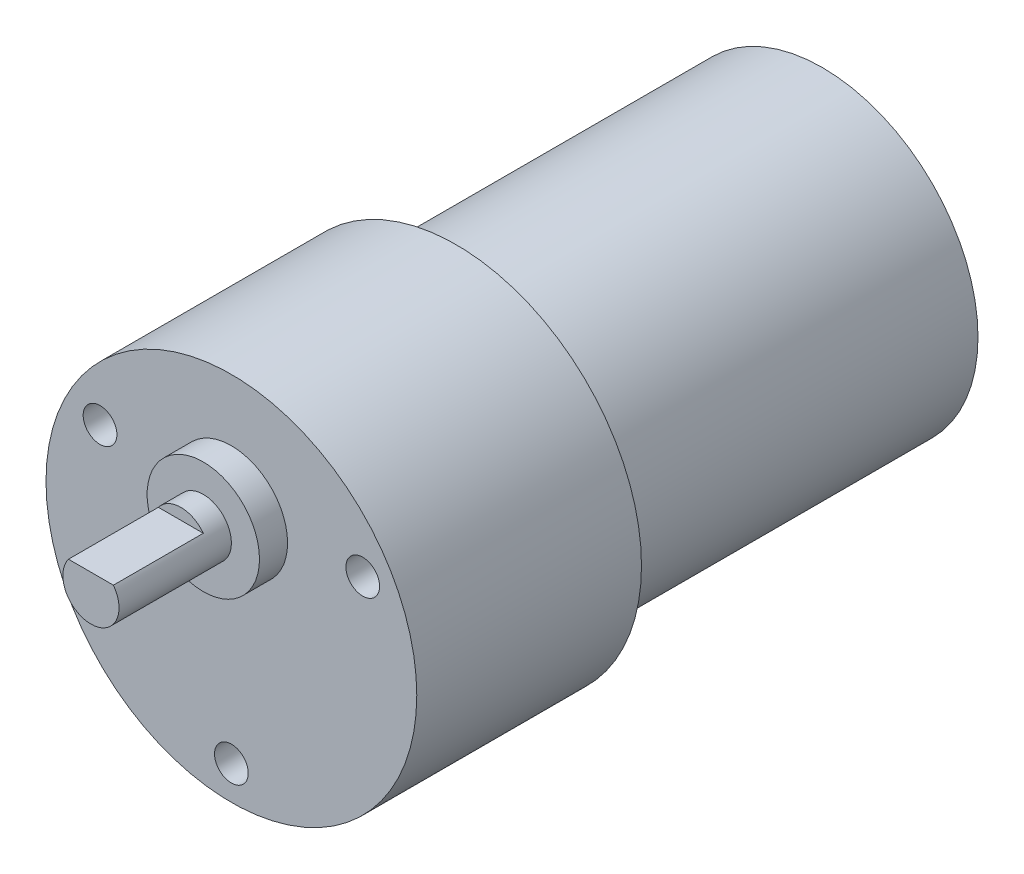
SolidWorks part; units mm, degrees
ref_plane "Front Plane" through (0, 0, 0) normal (0, 0, 1) x (1, 0, 0)
ref_plane "Top Plane" through (0, 0, 0) normal (0, 1, 0) x (1, 0, 0)
ref_plane "Right Plane" through (0, 0, 0) normal (1, 0, 0) x (0, 0, -1)
sketch "Sketch5" plane through (0, 0, 0) normal (1, 0, 0) x (0, 0, -1)
  line L0 (0, 0) -> (0, 16.5)
  line L1 (0, 16.5) -> (20, 16.5)
  line L2 (20, 16.5) -> (20, 13.85)
  line L3 (20, 13.85) -> (52.6, 13.85)
  line L4 (52.6, 13.85) -> (52.6, 5)
  line L5 (52.6, 5) -> (54.8, 5)
  line L6 (54.8, 5) -> (54.8, 1.15)
  line L7 (54.8, 1.15) -> (58.1, 1.15)
  line L8 (58.1, 1.15) -> (58.1, 0)
  line L9 (58.1, 0) -> (0, 0)
  line L10 (0, 0) -> (-50000, 0) construction
  dimension "D1" = 5.5
  dimension "D2" = 27.7
  dimension "D3" = 10
  dimension "D4" = 2.3
  dimension "D5" = 20
  dimension "D6" = 32.6
  dimension "D7" = 2.2
  dimension "33mm" = 33
revolve "Revolve1" add sketch "Sketch5" angle 360 about L10
sketch "Sketch6" plane through (0, 0, 0) normal (0, 0, 1) x (1, 0, 0)
  line L0 (-23.6587, 6) -> (49976.3413, 6) construction
  line L1 (0, 0) -> (0, 50000) construction
  circle A0 centre (0, 6) radius 5
  dimension "D2" = 10
  dimension "D1" = 6
extrude "Boss-Extrude3" add sketch "Sketch6" along normal blind 2.5
sketch "Sketch7" plane through (0, 0, 2.5) normal (0, 0, 1) x (1, 0, 0)
  circle A0 centre (0, 6) radius 2.5
  dimension "D1" = 5
extrude "Boss-Extrude4" add sketch "Sketch7" along normal blind 10
sketch "Sketch8" plane through (0, 0, 12.5) normal (0, 0, 1) x (1, 0, 0)
  line L0 (-2, 7.5) -> (2, 7.5)
  circle A0 centre (0, 6) radius 2.5 construction
  arc A1 (-2, 7.5) -> (2, 7.5) centre (0, 6) cw
  circle A3 centre (0, 6) radius 2.5 construction
  point P6 (1.1535, 7.4197)
  point P7 (0, 0)
  point P8 (0, 0)
  dimension "D1" = 1.5
extrude "Cut-Extrude1" cut sketch "Sketch8" against normal blind 8
sketch "Sketch9" plane through (0, 0, 0) normal (0, 0, 1) x (1, 0, 0)
  line L0 (0, 0) -> (0, -13.5) construction
  line L1 (0, 0) -> (-11.6913, 6.75) construction
  line L2 (0, 0) -> (11.6913, 6.75) construction
  line L3 (0, 0) -> (0, -13.5) construction
  line L4 (0, 0) -> (-11.6913, 6.75) construction
  circle A0 centre (0, 0) radius 13.5 construction
  circle A1 centre (0, -13.5) radius 1.5
  circle A2 centre (-11.6913, 6.75) radius 1.5
  circle A3 centre (11.6913, 6.75) radius 1.5
  point P8 (0, 0)
  dimension "D1" = 27
  dimension "D4" = 3
  dimension "D2" = 120
  dimension "D3" = 120
  dimension "D6" = 120
  dimension "D7" = 13.5
  dimension "D5" = 3
extrude "Cut-Extrude2" cut sketch "Sketch9" against normal blind 5
